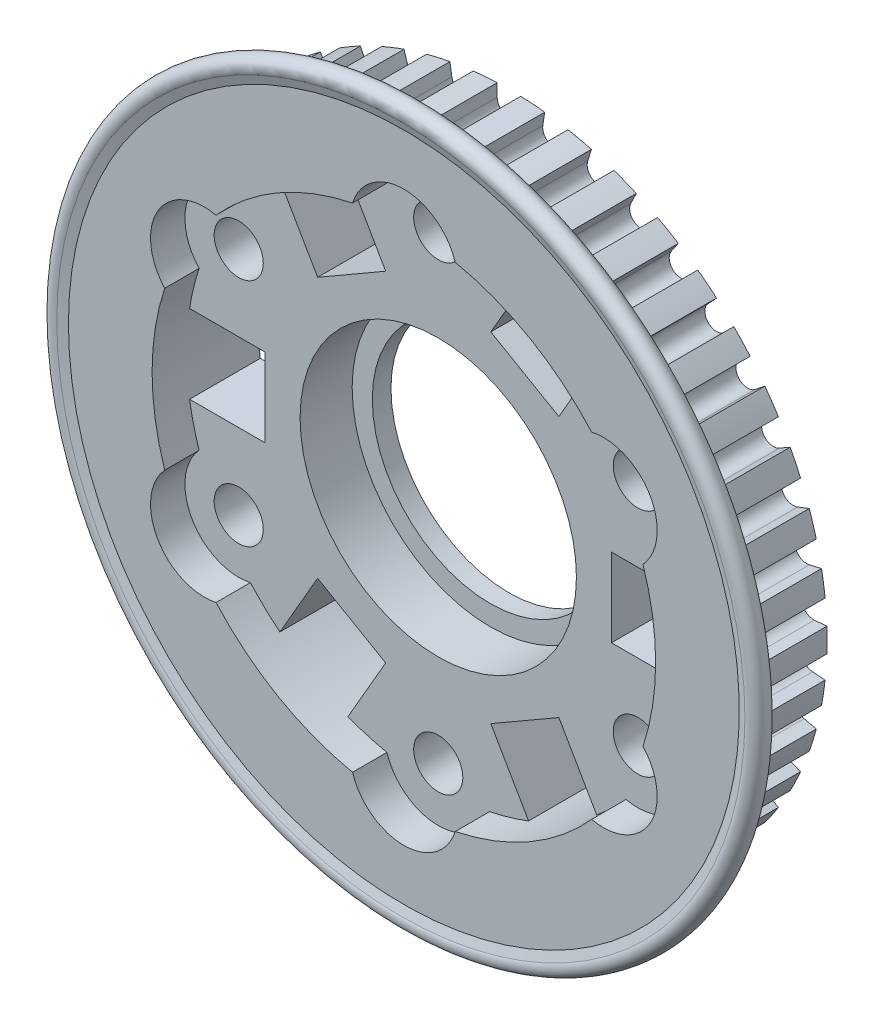
SolidWorks part; units mm, degrees
material "PC High Viscosity"
ref_plane "Plane X-Y" through (0, 0, 0) normal (0, 0, 1) x (1, 0, 0)
ref_plane "Plane Z-X" through (0, 0, 0) normal (0, 1, 0) x (1, 0, 0)
ref_plane "Plane Y-Z" through (0, 0, 0) normal (1, 0, 0) x (0, 0, -1)
ref_axis "Axis1" through (0, 0, -6.2167) along (0, 0, 1)
sketch "Sketch3" plane through (0, 0, 0) normal (1, 0, 0) x (0, 0, -1)
  line L0 (0, 0) -> (0, 34.6852)
  line L1 (0, 0) -> (10.8712, 0)
  line L2 (0, 34.6852) -> (-0.3124, 35.5774)
  line L3 (10.8712, 0) -> (10.8712, 32.893)
  line L4 (10.8712, 32.893) -> (2.6984, 32.893)
  line L5 (1.549, 36.3739) -> (2.6984, 32.893)
  arc A0 (1.549, 36.3739) -> (-0.3124, 35.5774) centre (0.5842, 36.0553) ccw
  dimension "D3" = 2.032
  dimension "D4" = 32.893
  dimension "D1" = 10.8712
  dimension "D2" = 0.4318
  dimension "D5" = 37.0713
revolve "Revolve1" add sketch "Sketch3" angle 360 about axis through (0, 0, -6.2167) along (0, 0, 1)
sketch "Sketch4" plane through (0, 0, 0) normal (1, 0, 0) x (0, 0, -1)
  line L0 (10.8712, -32.893) -> (10.8712, 32.893) construction
  line L1 (0, 34.6852) -> (0, -34.6852) construction
  line L2 (10.8712, 0) -> (10.8712, 12.2047)
  line L3 (0, 14.2875) -> (0, 0)
  line L4 (0, 14.2875) -> (8.9408, 14.2875)
  line L5 (8.9408, 14.2875) -> (8.9408, 12.2047)
  line L6 (8.9408, 12.2047) -> (10.8712, 12.2047)
  line L7 (10.8712, 0) -> (0, 0)
  line L8 (6.2167, 0) -> (-6.2167, 0) construction
  dimension "D1" = 14.2875
  dimension "D2" = 12.2047
  dimension "D3" = 1.9304
revolve "Cut-Revolve2" cut sketch "Sketch4" angle 360 about axis through (0, 0, -6.2167) along (0, 0, 1)
sketch "Sketch5" plane through (0, 0, 0) normal (0, 0, 1) x (1, 0, 0)
  arc A0 (-5.3082, 25.4881) -> (-19.4192, 17.3411) centre (0, 0) ccw
  arc A1 (5.3082, 25.4881) -> (-5.3082, 25.4881) centre (0, 23.8252) ccw
  arc A2 (24.7275, 8.147) -> (19.4192, 17.3411) centre (20.6332, 11.9126) ccw
  arc A3 (19.4192, -17.3411) -> (24.7275, -8.147) centre (20.6332, -11.9126) ccw
  arc A4 (-5.3082, -25.4881) -> (5.3082, -25.4881) centre (0, -23.8252) ccw
  arc A5 (-24.7275, -8.147) -> (-19.4192, -17.3411) centre (-20.6332, -11.9126) ccw
  arc A6 (-19.4192, 17.3411) -> (-24.7275, 8.147) centre (-20.6332, 11.9126) ccw
  arc A7 (19.4192, 17.3411) -> (5.3082, 25.4881) centre (0, 0) ccw
  arc A8 (24.7275, -8.147) -> (24.7275, 8.147) centre (0, 0) ccw
  arc A9 (5.3082, -25.4881) -> (19.4192, -17.3411) centre (0, 0) ccw
  arc A10 (-19.4192, -17.3411) -> (-5.3082, -25.4881) centre (0, 0) ccw
  arc A11 (-24.7275, 8.147) -> (-24.7275, -8.147) centre (0, 0) ccw
  point P24 (0, 0)
  dimension "D1" = 52.07
  dimension "D3" = 11.1252
  dimension "D2" = 23.8252
  dimension "D4" = 6
extrude "Cut-Extrude1" cut sketch "Sketch5" against normal blind 3.556
sketch "Sketch6" plane through (0, 0, -3.556) normal (0, 0, 1) x (1, 0, 0)
  line L0 (9.3384, 24.3026) -> (5.434, 17.5399)
  line L1 (16.3775, 20.2386) -> (12.473, 13.4759)
  line L2 (5.434, 17.5399) -> (12.473, 13.4759)
  line L3 (0, 0) -> (20.2695, 35.1077) construction
  line L4 (0, 0) -> (48.1678, 0) construction
  line L5 (25.7159, -4.064) -> (17.907, -4.064)
  line L6 (17.907, 4.064) -> (17.907, -4.064)
  line L7 (25.7159, 4.064) -> (17.907, 4.064)
  line L8 (9.3384, -24.3026) -> (5.434, -17.5399)
  line L9 (12.473, -13.4759) -> (5.434, -17.5399)
  line L10 (16.3775, -20.2386) -> (12.473, -13.4759)
  line L11 (-16.3775, -20.2386) -> (-12.473, -13.4759)
  line L12 (-5.434, -17.5399) -> (-12.473, -13.4759)
  line L13 (-9.3384, -24.3026) -> (-5.434, -17.5399)
  line L14 (-25.7159, 4.064) -> (-17.907, 4.064)
  line L15 (-17.907, -4.064) -> (-17.907, 4.064)
  line L16 (-25.7159, -4.064) -> (-17.907, -4.064)
  line L17 (-9.3384, 24.3026) -> (-5.434, 17.5399)
  line L18 (-12.473, 13.4759) -> (-5.434, 17.5399)
  line L19 (-16.3775, 20.2386) -> (-12.473, 13.4759)
  circle A0 centre (0, 23.8252) radius 2.54
  arc A1 (5.3082, 25.4881) -> (-5.3082, 25.4881) centre (0, 23.8252) ccw construction
  arc A2 (25.7159, -4.064) -> (25.7159, 4.064) centre (0, 0) ccw
  circle A3 centre (20.6332, 11.9126) radius 2.54
  arc A4 (9.3384, -24.3026) -> (16.3775, -20.2386) centre (0, 0) ccw
  circle A5 centre (20.6332, -11.9126) radius 2.54
  arc A6 (-16.3775, -20.2386) -> (-9.3384, -24.3026) centre (0, 0) ccw
  arc A7 (19.4192, 17.3411) -> (5.3082, 25.4881) centre (0, 0) ccw construction
  arc A8 (16.3775, 20.2386) -> (9.3384, 24.3026) centre (0, 0) ccw
  circle A9 centre (0, -23.8252) radius 2.54
  arc A10 (-25.7159, 4.064) -> (-25.7159, -4.064) centre (0, 0) ccw
  circle A11 centre (-20.6332, -11.9126) radius 2.54
  arc A12 (-9.3384, 24.3026) -> (-16.3775, 20.2386) centre (0, 0) ccw
  circle A13 centre (-20.6332, 11.9126) radius 2.54
  point P17 (0, 0)
  point P47 (0, 0)
  dimension "D1" = 5.08
  dimension "D6" = 17.907
  dimension "D3" = 8.128
  dimension "D4" = 60
  dimension "D5" = 4.064
  dimension "D2" = 6
extrude "Cut-Extrude2" cut sketch "Sketch6" against normal through all
sketch "Sketch7" plane through (0, 0, -10.8712) normal (0, 0, -1) x (-1, 0, 0)
  circle A0 centre (0, 23.8252) radius 4.1529
  dimension "D1" = 8.3058
extrude "Cut-Extrude3" cut sketch "Sketch7" against normal blind 1.397
sketch "Sketch8" plane through (0, 0, -10.8712) normal (0, 0, -1) x (-1, 0, 0)
  circle A0 centre (0, -23.8252) radius 4.1275
  circle A1 centre (0, -23.8252) radius 2.54 construction
  circle A2 centre (0, -23.8252) radius 2.54
  dimension "D1" = 8.255
extrude "Boss-Extrude2" add sketch "Sketch8" along normal blind 1.27
sketch "Sketch9" plane through (0, 0, -10.8712) normal (0, 0, -1) x (-1, 0, 0)
  line L0 (1.2192, 31.5722) -> (1.2192, 32.8704)
  line L1 (-1.2192, 31.5722) -> (-1.2192, 32.8704)
  line L2 (5.9112, 31.0379) -> (6.1047, 32.3215)
  line L3 (3.5, 31.4013) -> (3.6935, 32.685)
  line L4 (10.4711, 29.8102) -> (10.8538, 31.0507)
  line L5 (8.141, 30.5289) -> (8.5237, 31.7694)
  line L6 (14.7971, 27.9166) -> (15.3604, 29.0862)
  line L7 (12.6002, 28.9746) -> (13.1635, 30.1442)
  line L8 (18.7926, 25.3994) -> (19.5239, 26.472)
  line L9 (16.7779, 26.773) -> (17.5092, 27.8456)
  line L10 (22.3683, 22.3148) -> (23.2513, 23.2664)
  line L11 (20.5808, 23.9733) -> (21.4638, 24.925)
  line L12 (25.4443, 18.7317) -> (26.4593, 19.5411)
  line L13 (23.924, 20.6382) -> (24.939, 21.4476)
  line L14 (27.9519, 14.7302) -> (29.0762, 15.3793)
  line L15 (26.7327, 16.842) -> (27.857, 17.4911)
  line L16 (29.8352, 10.3997) -> (31.0436, 10.874)
  line L17 (28.9443, 12.6695) -> (30.1528, 13.1438)
  line L18 (31.0519, 5.8368) -> (32.3176, 6.1257)
  line L19 (30.5093, 8.2141) -> (31.775, 8.503)
  line L20 (31.575, 1.1436) -> (32.8696, 1.2406)
  line L21 (31.3928, 3.5752) -> (32.6874, 3.6722)
  line L22 (31.3928, -3.5752) -> (32.6874, -3.6722)
  line L23 (31.575, -1.1436) -> (32.8696, -1.2406)
  line L24 (30.5093, -8.2141) -> (31.775, -8.503)
  line L25 (31.0519, -5.8368) -> (32.3176, -6.1257)
  line L26 (28.9443, -12.6695) -> (30.1528, -13.1438)
  line L27 (29.8352, -10.3997) -> (31.0436, -10.874)
  line L28 (26.7327, -16.842) -> (27.857, -17.4911)
  line L29 (27.9519, -14.7302) -> (29.0762, -15.3793)
  line L30 (23.924, -20.6382) -> (24.939, -21.4476)
  line L31 (25.4443, -18.7317) -> (26.4593, -19.5411)
  line L32 (20.5808, -23.9733) -> (21.4638, -24.925)
  line L33 (22.3683, -22.3148) -> (23.2513, -23.2664)
  line L34 (16.7779, -26.773) -> (17.5092, -27.8456)
  line L35 (18.7926, -25.3994) -> (19.5239, -26.472)
  line L36 (12.6002, -28.9746) -> (13.1635, -30.1442)
  line L37 (14.7971, -27.9166) -> (15.3604, -29.0862)
  line L38 (8.141, -30.5289) -> (8.5237, -31.7694)
  line L39 (10.4711, -29.8102) -> (10.8538, -31.0507)
  line L40 (3.5, -31.4013) -> (3.6935, -32.685)
  line L41 (5.9112, -31.0379) -> (6.1047, -32.3215)
  line L42 (-1.2192, -31.5722) -> (-1.2192, -32.8704)
  line L43 (1.2192, -31.5722) -> (1.2192, -32.8704)
  line L44 (-5.9112, -31.0379) -> (-6.1047, -32.3215)
  line L45 (-3.5, -31.4013) -> (-3.6935, -32.685)
  line L46 (-10.4711, -29.8102) -> (-10.8538, -31.0507)
  line L47 (-8.141, -30.5289) -> (-8.5237, -31.7694)
  line L48 (-14.7971, -27.9166) -> (-15.3604, -29.0862)
  line L49 (-12.6002, -28.9746) -> (-13.1635, -30.1442)
  line L50 (-18.7926, -25.3994) -> (-19.5239, -26.472)
  line L51 (-16.7779, -26.773) -> (-17.5092, -27.8456)
  line L52 (-22.3683, -22.3148) -> (-23.2513, -23.2664)
  line L53 (-20.5808, -23.9733) -> (-21.4638, -24.925)
  line L54 (-25.4443, -18.7317) -> (-26.4593, -19.5411)
  line L55 (-23.924, -20.6382) -> (-24.939, -21.4476)
  line L56 (-27.9519, -14.7302) -> (-29.0762, -15.3793)
  line L57 (-26.7327, -16.842) -> (-27.857, -17.4911)
  line L58 (-29.8352, -10.3997) -> (-31.0436, -10.874)
  line L59 (-28.9443, -12.6695) -> (-30.1528, -13.1438)
  line L60 (-31.0519, -5.8368) -> (-32.3176, -6.1257)
  line L61 (-30.5093, -8.2141) -> (-31.775, -8.503)
  line L62 (-31.575, -1.1436) -> (-32.8696, -1.2406)
  line L63 (-31.3928, -3.5752) -> (-32.6874, -3.6722)
  line L64 (-31.3928, 3.5752) -> (-32.6874, 3.6722)
  line L65 (-31.575, 1.1436) -> (-32.8696, 1.2406)
  line L66 (-30.5093, 8.2141) -> (-31.775, 8.503)
  line L67 (-31.0519, 5.8368) -> (-32.3176, 6.1257)
  line L68 (-28.9443, 12.6695) -> (-30.1528, 13.1438)
  line L69 (-29.8352, 10.3997) -> (-31.0436, 10.874)
  line L70 (-26.7327, 16.842) -> (-27.857, 17.4911)
  line L71 (-27.9519, 14.7302) -> (-29.0762, 15.3793)
  line L72 (-23.924, 20.6382) -> (-24.939, 21.4476)
  line L73 (-25.4443, 18.7317) -> (-26.4593, 19.5411)
  line L74 (-20.5808, 23.9733) -> (-21.4638, 24.925)
  line L75 (-22.3683, 22.3148) -> (-23.2513, 23.2664)
  line L76 (-16.7779, 26.773) -> (-17.5092, 27.8456)
  line L77 (-18.7926, 25.3994) -> (-19.5239, 26.472)
  line L78 (-12.6002, 28.9746) -> (-13.1635, 30.1442)
  line L79 (-14.7971, 27.9166) -> (-15.3604, 29.0862)
  line L80 (-8.141, 30.5289) -> (-8.5237, 31.7694)
  line L81 (-10.4711, 29.8102) -> (-10.8538, 31.0507)
  line L82 (-3.5, 31.4013) -> (-3.6935, 32.685)
  line L83 (-5.9112, 31.0379) -> (-6.1047, 32.3215)
  arc A0 (-1.2192, 31.5722) -> (1.2192, 31.5722) centre (0, 31.5722) ccw
  circle A1 centre (0, 0) radius 32.893 construction
  arc A2 (1.2192, 32.8704) -> (-1.2192, 32.8704) centre (0, 0) ccw
  arc A3 (6.1047, 32.3215) -> (3.6935, 32.685) centre (0, 0) ccw
  arc A4 (3.5, 31.4013) -> (5.9112, 31.0379) centre (4.7056, 31.2196) ccw
  arc A5 (10.8538, 31.0507) -> (8.5237, 31.7694) centre (0, 0) ccw
  arc A6 (8.141, 30.5289) -> (10.4711, 29.8102) centre (9.3061, 30.1695) ccw
  arc A7 (15.3604, 29.0862) -> (13.1635, 30.1442) centre (0, 0) ccw
  arc A8 (12.6002, 28.9746) -> (14.7971, 27.9166) centre (13.6987, 28.4456) ccw
  arc A9 (19.5239, 26.472) -> (17.5092, 27.8456) centre (0, 0) ccw
  arc A10 (16.7779, 26.773) -> (18.7926, 25.3994) centre (17.7853, 26.0862) ccw
  arc A11 (23.2513, 23.2664) -> (21.4638, 24.925) centre (0, 0) ccw
  arc A12 (20.5808, 23.9733) -> (22.3683, 22.3148) centre (21.4745, 23.1441) ccw
  arc A13 (26.4593, 19.5411) -> (24.939, 21.4476) centre (0, 0) ccw
  arc A14 (23.924, 20.6382) -> (25.4443, 18.7317) centre (24.6841, 19.6849) ccw
  arc A15 (29.0762, 15.3793) -> (27.857, 17.4911) centre (0, 0) ccw
  arc A16 (26.7327, 16.842) -> (27.9519, 14.7302) centre (27.3423, 15.7861) ccw
  arc A17 (31.0436, 10.874) -> (30.1528, 13.1438) centre (0, 0) ccw
  arc A18 (28.9443, 12.6695) -> (29.8352, 10.3997) centre (29.3897, 11.5346) ccw
  arc A19 (32.3176, 6.1257) -> (31.775, 8.503) centre (0, 0) ccw
  arc A20 (30.5093, 8.2141) -> (31.0519, 5.8368) centre (30.7806, 7.0255) ccw
  arc A21 (32.8696, 1.2406) -> (32.6874, 3.6722) centre (0, 0) ccw
  arc A22 (31.3928, 3.5752) -> (31.575, 1.1436) centre (31.4839, 2.3594) ccw
  arc A23 (32.6874, -3.6722) -> (32.8696, -1.2406) centre (0, 0) ccw
  arc A24 (31.575, -1.1436) -> (31.3928, -3.5752) centre (31.4839, -2.3594) ccw
  arc A25 (31.775, -8.503) -> (32.3176, -6.1257) centre (0, 0) ccw
  arc A26 (31.0519, -5.8368) -> (30.5093, -8.2141) centre (30.7806, -7.0255) ccw
  arc A27 (30.1528, -13.1438) -> (31.0436, -10.874) centre (0, 0) ccw
  arc A28 (29.8352, -10.3997) -> (28.9443, -12.6695) centre (29.3897, -11.5346) ccw
  arc A29 (27.857, -17.4911) -> (29.0762, -15.3793) centre (0, 0) ccw
  arc A30 (27.9519, -14.7302) -> (26.7327, -16.842) centre (27.3423, -15.7861) ccw
  arc A31 (24.939, -21.4476) -> (26.4593, -19.5411) centre (0, 0) ccw
  arc A32 (25.4443, -18.7317) -> (23.924, -20.6382) centre (24.6841, -19.6849) ccw
  arc A33 (21.4638, -24.925) -> (23.2513, -23.2664) centre (0, 0) ccw
  arc A34 (22.3683, -22.3148) -> (20.5808, -23.9733) centre (21.4745, -23.1441) ccw
  arc A35 (17.5092, -27.8456) -> (19.5239, -26.472) centre (0, 0) ccw
  arc A36 (18.7926, -25.3994) -> (16.7779, -26.773) centre (17.7853, -26.0862) ccw
  arc A37 (13.1635, -30.1442) -> (15.3604, -29.0862) centre (0, 0) ccw
  arc A38 (14.7971, -27.9166) -> (12.6002, -28.9746) centre (13.6987, -28.4456) ccw
  arc A39 (8.5237, -31.7694) -> (10.8538, -31.0507) centre (0, 0) ccw
  arc A40 (10.4711, -29.8102) -> (8.141, -30.5289) centre (9.3061, -30.1695) ccw
  arc A41 (3.6935, -32.685) -> (6.1047, -32.3215) centre (0, 0) ccw
  arc A42 (5.9112, -31.0379) -> (3.5, -31.4013) centre (4.7056, -31.2196) ccw
  arc A43 (-1.2192, -32.8704) -> (1.2192, -32.8704) centre (0, 0) ccw
  arc A44 (1.2192, -31.5722) -> (-1.2192, -31.5722) centre (0, -31.5722) ccw
  arc A45 (-6.1047, -32.3215) -> (-3.6935, -32.685) centre (0, 0) ccw
  arc A46 (-3.5, -31.4013) -> (-5.9112, -31.0379) centre (-4.7056, -31.2196) ccw
  arc A47 (-10.8538, -31.0507) -> (-8.5237, -31.7694) centre (0, 0) ccw
  arc A48 (-8.141, -30.5289) -> (-10.4711, -29.8102) centre (-9.3061, -30.1695) ccw
  arc A49 (-15.3604, -29.0862) -> (-13.1635, -30.1442) centre (0, 0) ccw
  arc A50 (-12.6002, -28.9746) -> (-14.7971, -27.9166) centre (-13.6987, -28.4456) ccw
  arc A51 (-19.5239, -26.472) -> (-17.5092, -27.8456) centre (0, 0) ccw
  arc A52 (-16.7779, -26.773) -> (-18.7926, -25.3994) centre (-17.7853, -26.0862) ccw
  arc A53 (-23.2513, -23.2664) -> (-21.4638, -24.925) centre (0, 0) ccw
  arc A54 (-20.5808, -23.9733) -> (-22.3683, -22.3148) centre (-21.4745, -23.1441) ccw
  arc A55 (-26.4593, -19.5411) -> (-24.939, -21.4476) centre (0, 0) ccw
  arc A56 (-23.924, -20.6382) -> (-25.4443, -18.7317) centre (-24.6841, -19.6849) ccw
  arc A57 (-29.0762, -15.3793) -> (-27.857, -17.4911) centre (0, 0) ccw
  arc A58 (-26.7327, -16.842) -> (-27.9519, -14.7302) centre (-27.3423, -15.7861) ccw
  arc A59 (-31.0436, -10.874) -> (-30.1528, -13.1438) centre (0, 0) ccw
  arc A60 (-28.9443, -12.6695) -> (-29.8352, -10.3997) centre (-29.3897, -11.5346) ccw
  arc A61 (-32.3176, -6.1257) -> (-31.775, -8.503) centre (0, 0) ccw
  arc A62 (-30.5093, -8.2141) -> (-31.0519, -5.8368) centre (-30.7806, -7.0255) ccw
  arc A63 (-32.8696, -1.2406) -> (-32.6874, -3.6722) centre (0, 0) ccw
  arc A64 (-31.3928, -3.5752) -> (-31.575, -1.1436) centre (-31.4839, -2.3594) ccw
  arc A65 (-32.6874, 3.6722) -> (-32.8696, 1.2406) centre (0, 0) ccw
  arc A66 (-31.575, 1.1436) -> (-31.3928, 3.5752) centre (-31.4839, 2.3594) ccw
  arc A67 (-31.775, 8.503) -> (-32.3176, 6.1257) centre (0, 0) ccw
  arc A68 (-31.0519, 5.8368) -> (-30.5093, 8.2141) centre (-30.7806, 7.0255) ccw
  arc A69 (-30.1528, 13.1438) -> (-31.0436, 10.874) centre (0, 0) ccw
  arc A70 (-29.8352, 10.3997) -> (-28.9443, 12.6695) centre (-29.3897, 11.5346) ccw
  arc A71 (-27.857, 17.4911) -> (-29.0762, 15.3793) centre (0, 0) ccw
  arc A72 (-27.9519, 14.7302) -> (-26.7327, 16.842) centre (-27.3423, 15.7861) ccw
  arc A73 (-24.939, 21.4476) -> (-26.4593, 19.5411) centre (0, 0) ccw
  arc A74 (-25.4443, 18.7317) -> (-23.924, 20.6382) centre (-24.6841, 19.6849) ccw
  arc A75 (-21.4638, 24.925) -> (-23.2513, 23.2664) centre (0, 0) ccw
  arc A76 (-22.3683, 22.3148) -> (-20.5808, 23.9733) centre (-21.4745, 23.1441) ccw
  arc A77 (-17.5092, 27.8456) -> (-19.5239, 26.472) centre (0, 0) ccw
  arc A78 (-18.7926, 25.3994) -> (-16.7779, 26.773) centre (-17.7853, 26.0862) ccw
  arc A79 (-13.1635, 30.1442) -> (-15.3604, 29.0862) centre (0, 0) ccw
  arc A80 (-14.7971, 27.9166) -> (-12.6002, 28.9746) centre (-13.6987, 28.4456) ccw
  arc A81 (-8.5237, 31.7694) -> (-10.8538, 31.0507) centre (0, 0) ccw
  arc A82 (-10.4711, 29.8102) -> (-8.141, 30.5289) centre (-9.3061, 30.1695) ccw
  arc A83 (-3.6935, 32.685) -> (-6.1047, 32.3215) centre (0, 0) ccw
  arc A84 (-5.9112, 31.0379) -> (-3.5, 31.4013) centre (-4.7056, 31.2196) ccw
  point P215 (0, 0)
  dimension "D1" = 1.2192
  dimension "D2" = 2.54
  dimension "D3" = 42
extrude "Cut-Extrude4" cut sketch "Sketch9" against normal blind 8.1788
